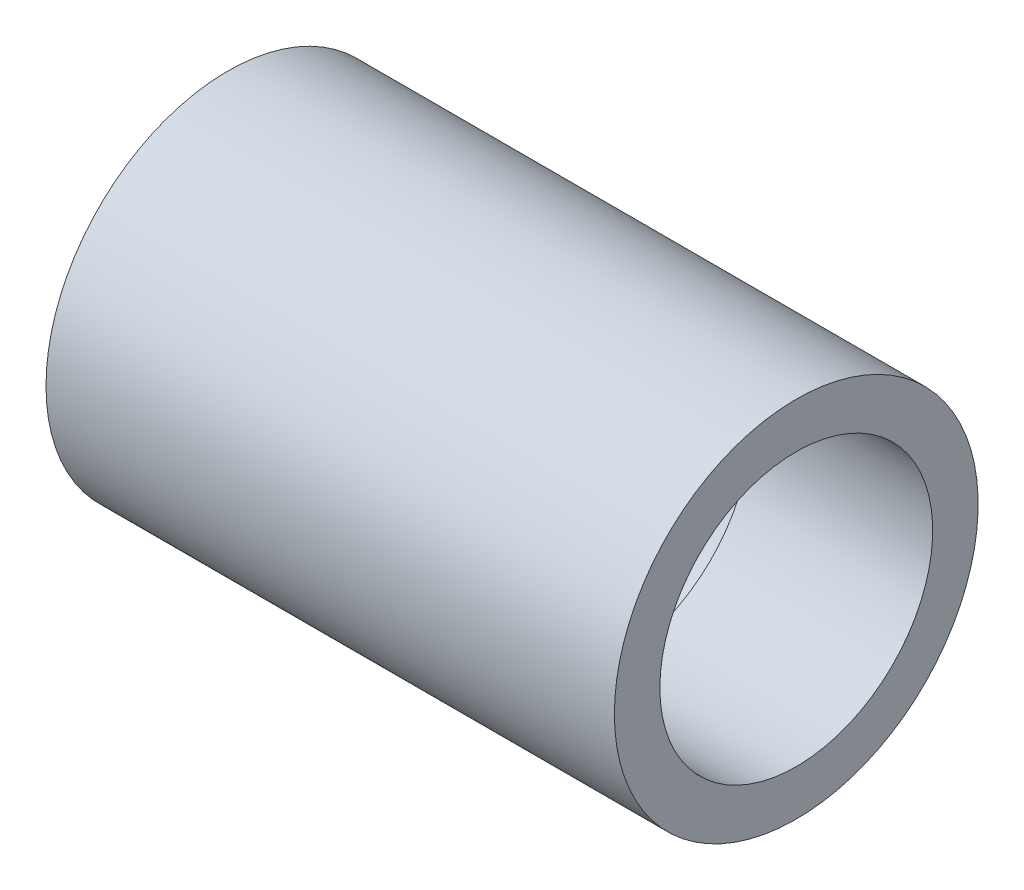
SolidWorks part; units mm, degrees
material "Prata pura"
ref_plane "Plano frontal" through (0, 0, 0) normal (0, 0, 1) x (1, 0, 0)
ref_plane "Plano superior" through (0, 0, 0) normal (0, 1, 0) x (1, 0, 0)
ref_plane "Plano direito" through (0, 0, 0) normal (1, 0, 0) x (0, 0, -1)
sketch "Esboço1" plane through (0, 0, 0) normal (0, 0, 1) x (1, 0, 0)
  line L0 (-6.2577, 0) -> (8.6354, 0) construction
  line L1 (-12.5, 6) -> (-4.5, 6)
  line L2 (-4.5, 6) -> (-4.5, 6.5)
  line L3 (-4.5, 6.5) -> (4.5, 6.5)
  line L4 (4.5, 6.5) -> (4.5, 6)
  line L5 (4.5, 6) -> (12.5, 6)
  line L6 (12.5, 6) -> (12.5, 8)
  line L7 (12.5, 8) -> (-12.5, 8)
  line L8 (-12.5, 8) -> (-12.5, 6)
  point P5 (6.7633, 6.2028)
  dimension "D1" = 8
  dimension "D2" = 12.5
  dimension "D3" = 12.5
  dimension "D4" = 6.5
  dimension "D5" = 6
  dimension "D6" = 6
  dimension "D7" = 4.5
  dimension "D8" = 4.5
revolve "Revolução1" add sketch "Esboço1" angle 360 about L0
